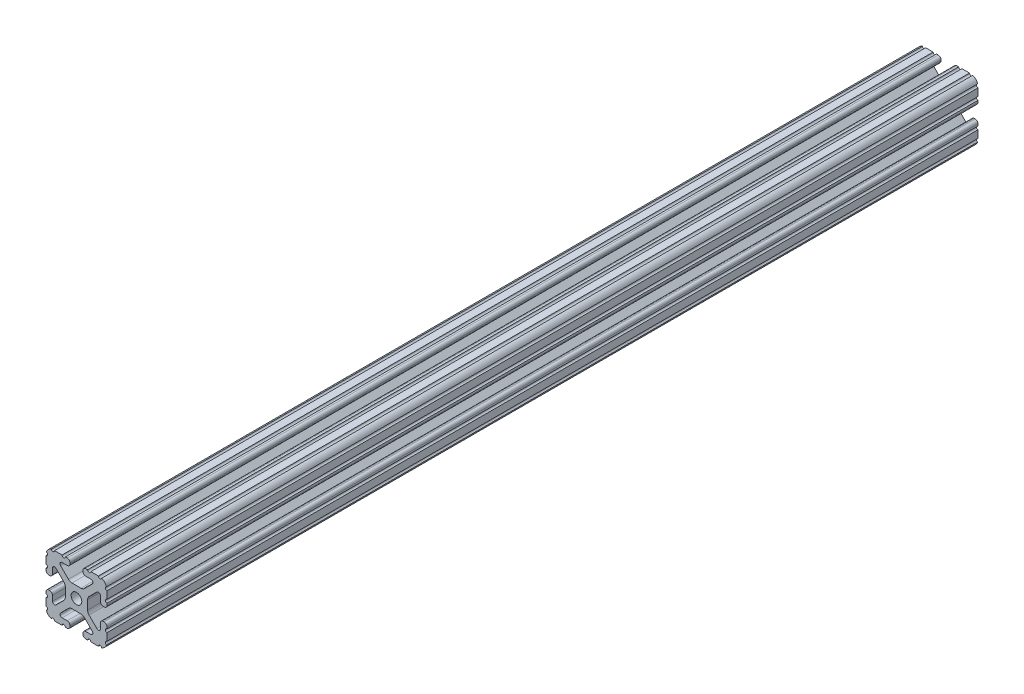
SolidWorks part; units mm, degrees
ref_plane "Front Plane" through (0, 0, 0) normal (0, 0, 1) x (1, 0, 0)
ref_plane "Top Plane" through (0, 0, 0) normal (0, 1, 0) x (1, 0, 0)
ref_plane "Right Plane" through (0, 0, 0) normal (1, 0, 0) x (0, 0, -1)
sketch "Sketch2" plane through (0, 0, 0) normal (0, 0, 1) x (1, 0, 0)
  line L0 (0, 19.05) -> (0, -19.05) construction
  line L1 (-19.05, 0) -> (19.05, 0) construction
  line L2 (4.064, -19.05) -> (19.05, -19.05)
  line L3 (19.05, -19.05) -> (19.05, -4.064)
  line L4 (4.064, -19.05) -> (4.064, -14.986)
  line L5 (4.064, -14.986) -> (12.1123, -14.986)
  line L6 (12.1123, -14.986) -> (4.1113, -6.985)
  line L7 (0, 0) -> (19.05, -19.05) construction
  line L8 (19.05, -4.064) -> (14.986, -4.064)
  line L9 (14.986, -4.064) -> (14.986, -12.1123)
  line L10 (14.986, -12.1123) -> (6.985, -4.1113)
  circle A0 centre (0, 0) radius 3.3274
  arc A1 (8.9963, -14.986) -> (9.909, -12.7826) centre (8.9963, -13.6953) ccw construction
  point P8 (0, -6.985)
  dimension "Center Hole Diameter" = 6.6548
  dimension "Rail Height" = 38.1
  dimension "Rail Width" = 38.1
  dimension "T-Slot Width" = 8.128
  dimension "Slot Inner Width" = 20.574
  dimension "Thickness" = 4.064
  dimension "Slot Depth" = 8.001
  dimension "D1" = 4.064
sketch "Sketch3" plane through (0, 0, 0) normal (1, 0, 0) x (0, 0, -1)
  line L0 (-272.5, -19.05) -> (272.5, -19.05) construction
  line L1 (-247.1, 0) -> (247.1, 0) construction
  dimension "Length" = 545
  dimension "D1" = 25.4
sketch "Sketch4" plane through (0, 0, 0) normal (0, 0, 1) x (1, 0, 0)
  line L0 (5.7912, -19.05) -> (14.3002, -19.05)
  line L1 (4.064, -19.05) -> (19.05, -19.05) construction
  line L2 (4.064, -19.05) -> (4.064, -14.986) construction
  line L3 (4.064, -14.986) -> (12.1123, -14.986) construction
  line L4 (4.064, -16.7132) -> (4.064, -17.3228)
  line L5 (5.7912, -14.986) -> (8.9963, -14.986)
  line L6 (0, -6.985) -> (2.833, -6.985)
  line L7 (12.1123, -14.986) -> (4.1113, -6.985) construction
  line L8 (5.0152, -7.8889) -> (9.909, -12.7826)
  line L9 (19.05, -19.05) -> (19.05, -4.064) construction
  line L10 (14.986, -12.1123) -> (6.985, -4.1113) construction
  line L11 (14.986, -4.064) -> (14.986, -12.1123) construction
  line L12 (14.986, -8.9963) -> (14.986, -5.7912)
  line L13 (19.05, -4.064) -> (14.986, -4.064) construction
  line L14 (16.7132, -4.064) -> (17.3228, -4.064)
  line L15 (19.05, -5.7912) -> (19.05, -14.3002)
  line L16 (12.7826, -9.909) -> (7.8889, -5.0152)
  line L17 (6.985, 0) -> (6.985, -2.833)
  line L18 (-19.05, 0) -> (19.05, 0) construction
  line L19 (0, -6.985) -> (0, -3.3274)
  line L20 (0, 19.05) -> (0, -19.05) construction
  line L21 (6.985, 0) -> (3.3274, 0)
  arc A0 (4.064, -17.3228) -> (5.7912, -19.05) centre (5.7912, -17.3228) ccw
  arc A2 (4.064, -16.7132) -> (5.7912, -14.986) centre (5.7912, -16.7132) cw
  arc A3 (8.9963, -14.986) -> (9.909, -12.7826) centre (8.9963, -13.6953) ccw
  arc A4 (2.833, -6.985) -> (5.0152, -7.8889) centre (2.833, -10.0711) cw
  arc A5 (14.3002, -19.05) -> (19.05, -14.3002) centre (14.3002, -14.3002) ccw
  arc A6 (12.7826, -9.909) -> (14.986, -8.9963) centre (13.6953, -8.9963) ccw
  arc A7 (14.986, -5.7912) -> (16.7132, -4.064) centre (16.7132, -5.7912) cw
  arc A8 (17.3228, -4.064) -> (19.05, -5.7912) centre (17.3228, -5.7912) cw
  arc A9 (7.8889, -5.0152) -> (6.985, -2.833) centre (10.0711, -2.833) cw
  circle A10 centre (0, 0) radius 3.3274 construction
  arc A11 (0, -3.3274) -> (3.3274, 0) centre (0, 0) ccw
  dimension "D1" = 4.7498
  dimension "D2" = 3.0861
  dimension "D3" = 1.7272
extrude "Boss-Extrude1" add sketch "Sketch4" along normal mid plane 545
sketch "Sketch5" plane through (0, 0, 0) normal (0, 0, 1) x (1, 0, 0)
  line L0 (4.064, -19.05) -> (19.05, -19.05) construction
  line L1 (5.7912, -14.986) -> (8.9963, -14.986) construction
  line L3 (0, 0) -> (19.05, -19.05) construction
  line L4 (8.9963, -14.986) -> (8.9963, -19.05) construction
  line L5 (12.1123, -14.986) -> (4.1113, -6.985) construction
  circle A0 centre (14.7395, -19.05) radius 1.016
  circle A1 centre (7.9803, -19.05) radius 1.016
  circle A2 centre (19.05, -14.7395) radius 1.016
  circle A3 centre (19.05, -7.9803) radius 1.016
  point P10 (7.3938, -14.986)
  point P12 (13.6953, -8.9963)
  dimension "D1" = 2.032
extrude "Cut-Extrude1" cut sketch "Sketch5" against normal through all both and the other way through all
mirror "Mirror1" about plane through (0, 0, 0) normal (1, 0, 0) of bodies 137 134
mirror "Mirror2" about plane through (0, 0, 0) normal (0, 1, 0) of bodies 135
equation "\"D1@Boss-Extrude1\"=\"Length@Sketch3\""
equation "\"D1@Sketch2\"=\"Thickness@Sketch2\""
equation "\"D2@Sketch4\"=\"Slot Inner Width@Sketch2\"*0.15"
equation "\"D1@Sketch4\"=\"D3@Sketch4\"*2.75"
equation "\"D3@Sketch4\"=\"Thickness@Sketch2\"*0.425"
equation "\"D1@Sketch5\"=\"Thickness@Sketch2\"*0.5"
